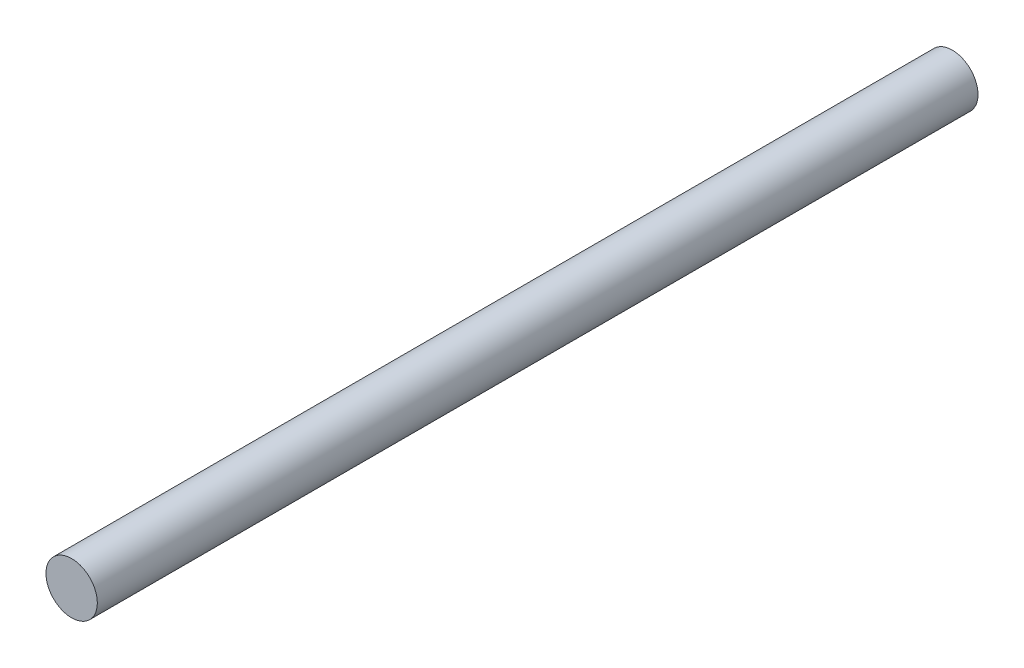
SolidWorks part; units mm, degrees
ref_plane "Front Plane" through (0, 0, 0) normal (0, 0, 1) x (1, 0, 0)
ref_plane "Top Plane" through (0, 0, 0) normal (0, 1, 0) x (1, 0, 0)
ref_plane "Right Plane" through (0, 0, 0) normal (1, 0, 0) x (0, 0, -1)
sketch "Sketch1" plane through (0, 0, 0) normal (0, 0, 1) x (1, 0, 0)
  circle A0 centre (0, 0) radius 3.5
  dimension "D1" = 7
extrude "Boss-Extrude1" add sketch "Sketch1" along normal blind 120
